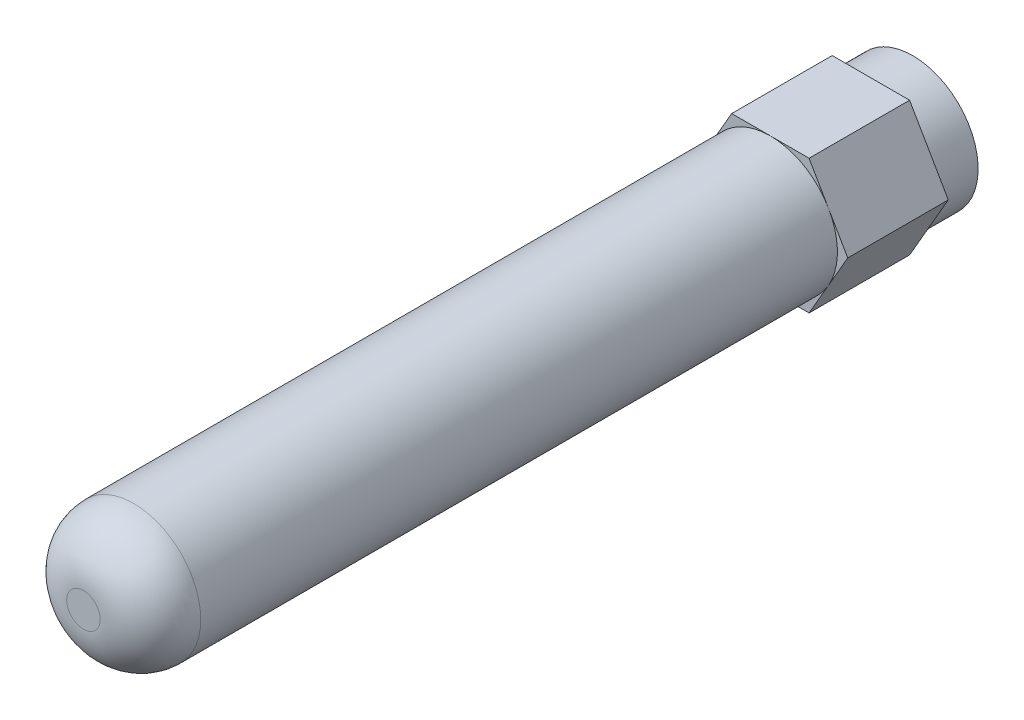
SolidWorks part; units mm, degrees
ref_plane "Alzado" through (0, 0, 0) normal (0, 0, 1) x (1, 0, 0)
ref_plane "Planta" through (0, 0, 0) normal (0, 1, 0) x (1, 0, 0)
ref_plane "Vista lateral" through (0, 0, 0) normal (1, 0, 0) x (0, 0, -1)
sketch "Croquis1" plane through (0, 0, 0) normal (0, 0, 1) x (1, 0, 0)
  circle A0 centre (0, 0) radius 4
  dimension "D1" = 8
extrude "Saliente-Extruir1" add sketch "Croquis1" along normal blind 41
sketch "Croquis2" plane through (0, 0, 0) normal (0, 0, -1) x (-1, 0, 0)
  line L0 (0, 0) -> (0, 4) construction
  line L1 (-2.3094, 4) -> (-4.6188, 0)
  line L2 (-4.6188, 0) -> (-2.3094, -4)
  line L3 (-2.3094, -4) -> (2.3094, -4)
  line L4 (2.3094, -4) -> (4.6188, 0)
  line L5 (4.6188, 0) -> (2.3094, 4)
  line L6 (2.3094, 4) -> (-2.3094, 4)
  circle A0 centre (0, 0) radius 4 construction
  point P1 (0, 0)
  point P11 (0, 4)
  dimension "D1" = 8
extrude "Saliente-Extruir2" add sketch "Croquis2" along normal blind 6
sketch "Croquis3" plane through (0, 0, -6) normal (0, 0, -1) x (-1, 0, 0)
  circle A0 centre (0, 0) radius 3.9
  dimension "D1" = 7.8
extrude "Saliente-Extruir3" add sketch "Croquis3" along normal blind 2.5
fillet "Redondeo1" radius 3 1 edges at (4, 0, 41)
